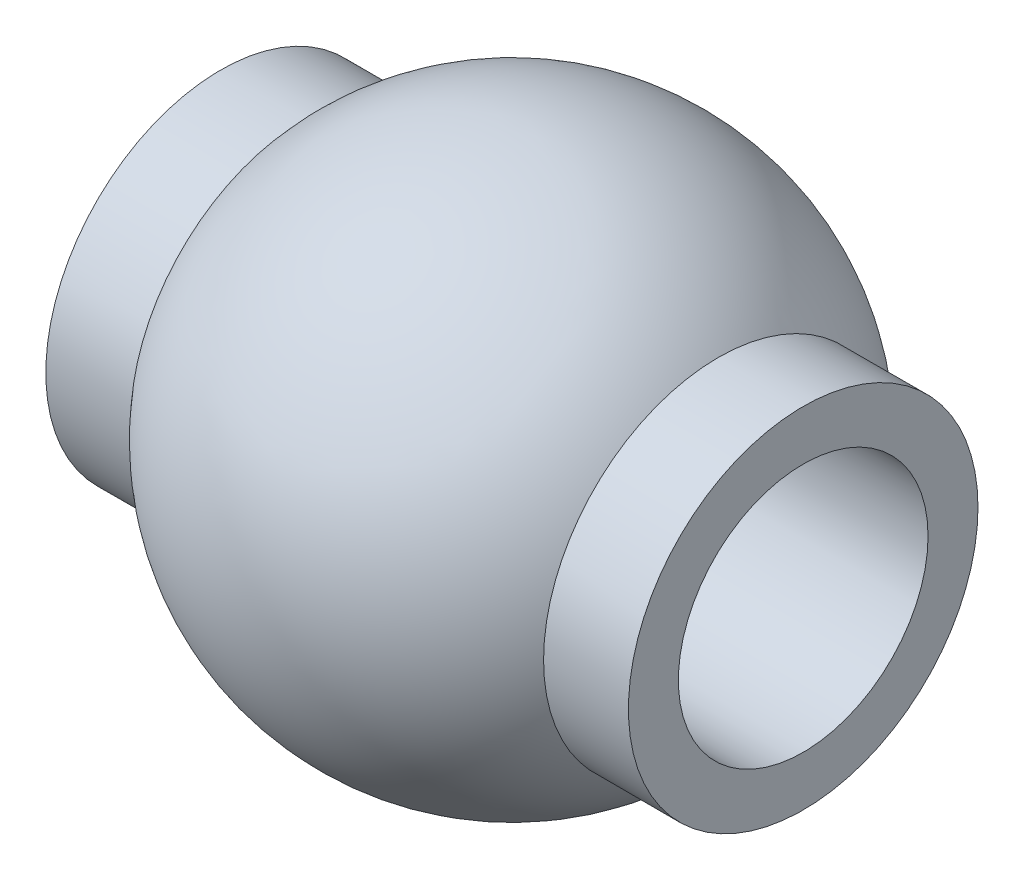
SolidWorks part; units mm, degrees
material "Alloy Steel"
ref_plane "X-Y Datum" through (0, 0, 0) normal (0, 0, 1) x (1, 0, 0)
ref_plane "X-Z Datum" through (0, 0, 0) normal (0, 1, 0) x (1, 0, 0)
ref_plane "Y-Z Datum" through (0, 0, 0) normal (1, 0, 0) x (0, 0, -1)
sketch "Sketch2" plane through (0, 0, 0) normal (0, 1, 0) x (1, 0, 0)
  line L0 (0, 10.3187) -> (0, -10.3187)
  arc A0 (0, -10.3187) -> (0, 10.3187) centre (0, 0) ccw
  dimension "D1" = 20.6375
revolve "Revolve1" add sketch "Sketch2" angle 360 about L0
sketch "Sketch3" plane through (0, 0, 0) normal (1, 0, 0) x (0, 0, -1)
  circle A0 centre (0, 0) radius 6.6675
  circle A1 centre (0, 0) radius 4.7625
  dimension "D1" = 13.335
  dimension "D2" = 9.525
extrude "Boss-Extrude1" add sketch "Sketch3" along normal blind 11.1125 and the other way blind 11.1125
sketch "Sketch4" plane through (11.1125, 0, 0) normal (1, 0, 0) x (0, 0, -1)
  circle A0 centre (0, 0) radius 4.7625
extrude "Cut-Extrude1" cut sketch "Sketch4" against normal through all
